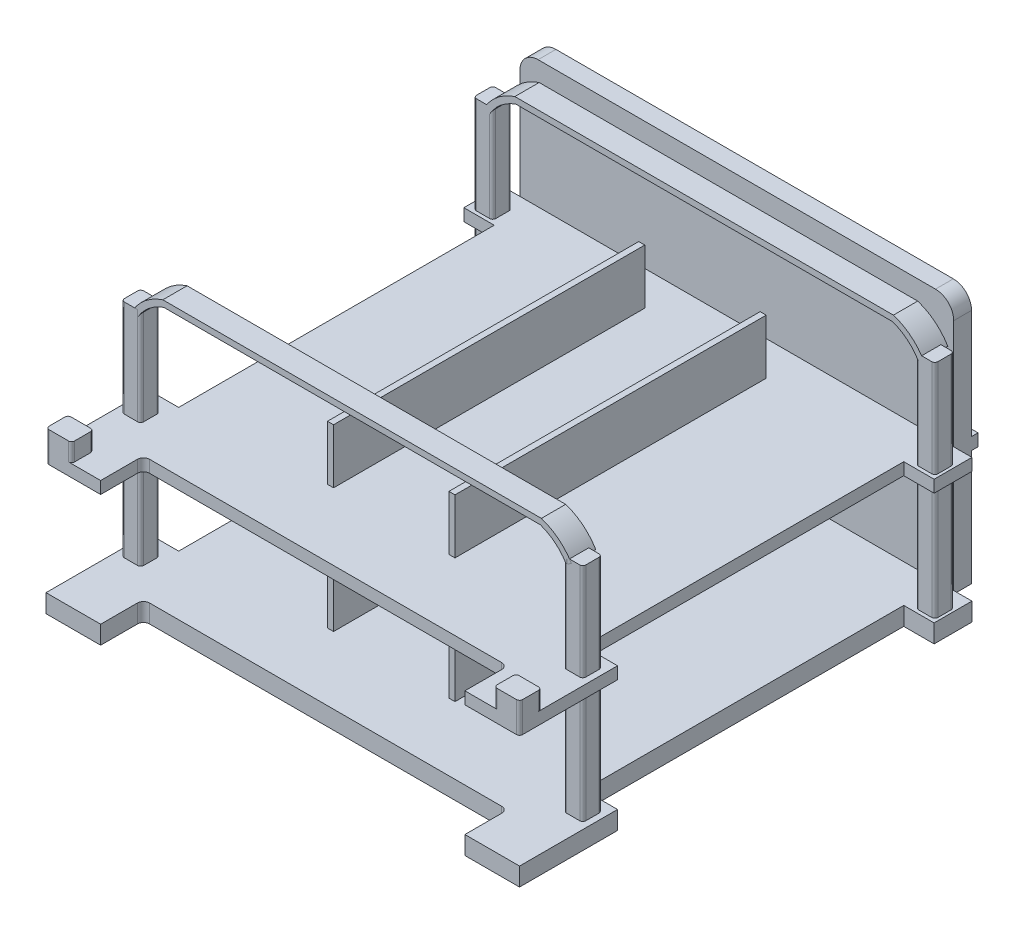
SolidWorks part; units mm, degrees
ref_plane "Front Plane" through (0, 0, 0) normal (0, 0, 1) x (1, 0, 0)
ref_plane "Top Plane" through (0, 0, 0) normal (0, 1, 0) x (1, 0, 0)
ref_plane "Right Plane" through (0, 0, 0) normal (1, 0, 0) x (0, 0, -1)
sketch "Sketch1" plane through (0, 0, 0) normal (0, 1, 0) x (1, 0, 0)
  line L0 (0, 0) -> (9, 0)
  line L1 (9, 0) -> (9, 6.0585)
  line L2 (10, 7.0585) -> (68, 7.0585)
  line L3 (69, 6.0585) -> (69, 0)
  line L4 (69, 0) -> (78, 0)
  line L5 (78, 0) -> (78, 16.147)
  line L6 (78, 16.147) -> (72.4592, 16.147)
  line L7 (72.4592, 16.147) -> (72.4592, 68.829)
  line L8 (72.4592, 68.829) -> (77.4592, 68.829)
  line L9 (77.4592, 68.829) -> (77.4592, 75.0585)
  line L10 (77.4592, 75.0585) -> (0, 75.0585)
  line L11 (0, 75.0585) -> (0, 68.829)
  line L12 (0, 68.829) -> (5, 68.829)
  line L13 (5, 68.829) -> (5, 16.8497)
  line L14 (5, 16.8497) -> (0, 16.8497)
  line L15 (0, 16.8497) -> (0, 0)
  arc A0 (9, 6.0585) -> (10, 7.0585) centre (10, 6.0585) cw
  arc A1 (69, 6.0585) -> (68, 7.0585) centre (68, 6.0585) ccw
  point P19 (9, 7.0585)
  point P22 (69, 7.0585)
  dimension "D7" = 1
  dimension "D8" = 1
  dimension "D1" = 60
  dimension "D2" = 4
  dimension "D3" = 3.4592
  dimension "D4" = 9
  dimension "D5" = 9
  dimension "D6" = 68
extrude "Boss-Extrude1" add sketch "Sketch1" along normal blind 2
sketch "Sketch2" plane through (0, 2, 0) normal (0, 1, 0) x (1, 0, 0)
  line L0 (1, 14.5922) -> (1, 11.4189)
  line L1 (1, 11.4189) -> (4.1733, 11.4189)
  line L2 (4.1733, 11.4189) -> (4.1733, 14.5922)
  line L3 (4.1733, 14.5922) -> (1, 14.5922)
  line L4 (39, 7.0585) -> (39, 14.1654) construction
  line L5 (10, 7.0585) -> (68, 7.0585) construction
  line L6 (73.8267, 11.4189) -> (73.8267, 14.5922)
  line L7 (77, 11.4189) -> (73.8267, 11.4189)
  line L8 (77, 14.5922) -> (77, 11.4189)
  line L9 (73.8267, 14.5922) -> (77, 14.5922)
  line L10 (5, 22.5675) -> (72.4592, 22.5675) construction
  line L11 (5, 68.829) -> (5, 16.8497) construction
  line L12 (72.4592, 16.147) -> (72.4592, 68.829) construction
  line L13 (0, 16.8497) -> (0, 0) construction
  dimension "D1" = 1
extrude "Boss-Extrude2" add sketch "Sketch2" along normal blind 16
sketch "Sketch3" plane through (0, 0, -11.4189) normal (0, 0, 1) x (1, 0, 0)
  line L0 (7.9846, 20.4783) -> (70.0154, 20.4783)
  line L1 (10, 2) -> (68, 2) construction
  line L2 (39, 20.4783) -> (39, -1.4193) construction
  line L3 (1, 18) -> (4.1733, 18) construction
  arc A0 (3.7238, 17) -> (7.9846, 20.4783) centre (10.609, 12.9147) cw
  arc A1 (74.2762, 17) -> (70.0154, 20.4783) centre (67.391, 12.9147) ccw
  point P3 (0, 0)
  point P7 (39, 2)
  point P14 (4.1229, 17)
  point P15 (7.1416, 20.6069)
  point P16 (6.236, 21.0597)
  point P17 (7.9846, 20.4783)
  point P18 (74.2762, 17)
  dimension "D1" = 1
extrude "Extrude-Thin1" add sketch "Sketch3" against normal blind 4 separate body thin thin type one direction wall 1
ref_plane "Plane1" through (0, 0, -42) normal (0, 0, 1) x (1, 0, 0)
mirror "Mirror1" about plane through (0, 0, -42) normal (0, 0, 1) of "Extrude-Thin1", "Boss-Extrude2"
sketch "Sketch4" plane through (0, 0, -69.4078) normal (0, 0, 1) x (1, 0, 0)
  line L0 (7.9846, 20.4783) -> (70.0154, 20.4783) construction
  line L1 (7.9846, 20.4783) -> (70.0154, 20.4783)
  arc A0 (74.2762, 17) -> (70.0154, 20.4783) centre (67.391, 12.9147) ccw construction
  arc A1 (7.9846, 20.4783) -> (3.7238, 17) centre (10.609, 12.9147) ccw construction
  arc A2 (74.2762, 17) -> (70.0154, 20.4783) centre (67.391, 12.9147) ccw
  arc A3 (7.9846, 20.4783) -> (3.7238, 17) centre (10.609, 12.9147) ccw
extrude "Extrude-Thin2" add sketch "Sketch4" against normal blind 4 thin thin type one direction wall 1
ref_plane "Plane2" through (0, -20, 0) normal (0, -1, 0) x (-1, 0, 0)
sketch "Sketch6" plane through (0, -20, 0) normal (0, -1, 0) x (-1, 0, 0)
  line L16 (-9, 6.0585) -> (-9, 0)
  line L17 (-9, 0) -> (0, 0)
  line L18 (0, 0) -> (0, 16.8497)
  line L19 (0, 16.8497) -> (-5, 16.8497)
  line L20 (-5, 16.8497) -> (-5, 68.829)
  line L21 (-5, 68.829) -> (0, 68.829)
  line L22 (0, 68.829) -> (0, 75.0585)
  line L23 (0, 75.0585) -> (-77.4592, 75.0585)
  line L24 (-77.4592, 75.0585) -> (-77.4592, 68.829)
  line L25 (-77.4592, 68.829) -> (-72.4592, 68.829)
  line L26 (-72.4592, 68.829) -> (-72.4592, 16.147)
  line L27 (-72.4592, 16.147) -> (-78, 16.147)
  line L28 (-78, 16.147) -> (-78, 0)
  line L29 (-78, 0) -> (-69, 0)
  line L30 (-69, 0) -> (-69, 6.0585)
  line L31 (-68, 7.0585) -> (-10, 7.0585)
  line L32 (-9, 6.0585) -> (-9, 0)
  line L33 (-9, 0) -> (0, 0)
  line L34 (0, 0) -> (0, 16.8497)
  line L35 (0, 16.8497) -> (-5, 16.8497)
  line L36 (-5, 16.8497) -> (-5, 68.829)
  line L37 (-5, 68.829) -> (0, 68.829)
  line L38 (0, 68.829) -> (0, 75.0585)
  line L39 (0, 75.0585) -> (-77.4592, 75.0585)
  line L40 (-77.4592, 75.0585) -> (-77.4592, 68.829)
  line L41 (-77.4592, 68.829) -> (-72.4592, 68.829)
  line L42 (-72.4592, 68.829) -> (-72.4592, 16.147)
  line L43 (-72.4592, 16.147) -> (-78, 16.147)
  line L44 (-78, 16.147) -> (-78, 0)
  line L45 (-78, 0) -> (-69, 0)
  line L46 (-69, 0) -> (-69, 6.0585)
  line L47 (-68, 7.0585) -> (-10, 7.0585)
  arc A2 (-68, 7.0585) -> (-69, 6.0585) centre (-68, 6.0585) ccw
  arc A3 (-9, 6.0585) -> (-10, 7.0585) centre (-10, 6.0585) ccw
  arc A4 (-68, 7.0585) -> (-69, 6.0585) centre (-68, 6.0585) ccw
  arc A5 (-9, 6.0585) -> (-10, 7.0585) centre (-10, 6.0585) ccw
  dimension "D1" = 0
extrude "Boss-Extrude3" add sketch "Sketch6" against normal mid plane 3 separate body
sketch "Sketch7" plane through (0, -18.5, 0) normal (0, 1, 0) x (1, 0, 0)
  line L0 (73.8267, 69.4078) -> (73.8267, 72.5811) construction
  line L1 (77, 69.4078) -> (73.8267, 69.4078) construction
  line L2 (73.8267, 72.5811) -> (77, 72.5811) construction
  line L3 (77, 72.5811) -> (77, 69.4078) construction
  line L4 (73.8267, 14.5922) -> (73.8267, 11.4189)
  line L5 (77, 14.5922) -> (73.8267, 14.5922)
  line L6 (77, 11.4189) -> (77, 14.5922)
  line L7 (73.8267, 11.4189) -> (77, 11.4189)
  line L8 (73.8267, 14.5922) -> (73.8267, 11.4189)
  line L9 (77, 14.5922) -> (73.8267, 14.5922)
  line L10 (77, 11.4189) -> (77, 14.5922)
  line L11 (73.8267, 11.4189) -> (77, 11.4189)
  line L12 (1, 14.5922) -> (1, 11.4189)
  line L13 (1, 11.4189) -> (4.1733, 11.4189)
  line L14 (4.1733, 11.4189) -> (4.1733, 14.5922)
  line L15 (4.1733, 14.5922) -> (1, 14.5922)
  line L16 (1, 14.5922) -> (1, 11.4189)
  line L17 (1, 11.4189) -> (4.1733, 11.4189)
  line L18 (4.1733, 11.4189) -> (4.1733, 14.5922)
  line L19 (4.1733, 14.5922) -> (1, 14.5922)
  line L24 (73.8267, 69.4078) -> (73.8267, 72.5811)
  line L25 (77, 69.4078) -> (73.8267, 69.4078)
  line L26 (73.8267, 72.5811) -> (77, 72.5811)
  line L27 (77, 72.5811) -> (77, 69.4078)
  line L33 (4.1733, 69.4078) -> (1, 69.4078) construction
  line L34 (4.1733, 72.5811) -> (4.1733, 69.4078) construction
  line L35 (1, 72.5811) -> (4.1733, 72.5811) construction
  line L36 (1, 69.4078) -> (1, 72.5811) construction
  line L37 (4.1733, 69.4078) -> (1, 69.4078)
  line L38 (4.1733, 72.5811) -> (4.1733, 69.4078)
  line L39 (1, 72.5811) -> (4.1733, 72.5811)
  line L40 (1, 69.4078) -> (1, 72.5811)
  dimension "D1" = 0
  dimension "D2" = 0
extrude "Boss-Extrude4" add sketch "Sketch7" along normal up to surface (18.5 mm away) up to face at (38.8798, 0, -28.7819)
sketch "Sketch8" plane through (0, 2, 0) normal (0, 1, 0) x (1, 0, 0)
  line L0 (39, 7.0585) -> (39, 14.1654) construction
  line L1 (0, 0) -> (4.2068, 0)
  line L2 (0, 0) -> (0, 3.6268)
  line L3 (0, 3.6268) -> (4.2068, 3.6268)
  line L4 (4.2068, 0) -> (4.2068, 3.6268)
  line L5 (39, 7.0585) -> (39, 14.1654) construction
  line L6 (78, 3.6268) -> (73.7932, 3.6268)
  line L7 (73.7932, 0) -> (73.7932, 3.6268)
  line L8 (78, 0) -> (73.7932, 0)
  line L9 (78, 0) -> (78, 3.6268)
extrude "Boss-Extrude5" add sketch "Sketch8" along normal blind 3
fillet "Fillet2" radius 0.5 40 edges at (77, -9.25, -11.4189) (1, -9.25, -14.5922) (1, -9.25, -11.4189) (4.1733, -9.25, -11.4189) (73.8267, -9.25, -11.4189) (73.8267, -9.25, -14.5922) (4.1733, -9.25, -14.5922) (77, -9.25, -14.5922) (77, -9.25, -69.4078) (73.8267, -9.25, -69.4078) (73.8267, -9.25, -72.5811) (77, -9.25, -72.5811) (78, 2.5, 0) (73.7932, 3.5, 0) (78, 3.5, -3.6268) (73.7932, 3.5, -3.6268) (73.8267, 10, -11.4189) (73.8267, 10, -14.5922) (77, 10, -14.5922) (77, 10, -11.4189) (73.8267, 9.8384, -72.5811) (73.8267, 9.8384, -69.4078) (77, 10, -72.5811) (77, 10, -69.4078) (4.1733, 9.8384, -72.5811) (4.1733, 9.8384, -69.4078) (1, 10, -72.5811) (1, 10, -69.4078) (4.1733, 10, -14.5922) (4.1733, 10, -11.4189) (1, 10, -14.5922) (1, 10, -11.4189) (0, 3.5, -3.6268) (4.2068, 3.5, -3.6268) (4.2068, 3.5, 0) (0, 2.5, 0) (1, -9.25, -72.5811) (4.1733, -9.25, -72.5811) (4.1733, -9.25, -69.4078) (1, -9.25, -69.4078)
sketch "Sketch9" plane through (0, 0, -75.0585) normal (0, 0, -1) x (-1, 0, 0)
  line L0 (-74.4592, 2) -> (-74.4592, 0)
  line L1 (-77.4592, 2) -> (0, 2) construction
  line L2 (-77.4592, 0) -> (0, 0) construction
  line L3 (-74.4592, 0) -> (-3, 0)
  line L4 (-3, 0) -> (-3, 2)
  line L5 (-3, 2) -> (-74.4592, 2)
  line L6 (-77.4592, 2) -> (-77.4592, 0) construction
  line L7 (0, 2) -> (0, 0) construction
  dimension "D1" = 3
  dimension "D2" = 3
extrude "Boss-Extrude6" add sketch "Sketch9" along normal blind 4
sketch "Sketch10" plane through (0, 2, 0) normal (0, 1, 0) x (1, 0, 0)
  line L0 (3, 75.0585) -> (74.4592, 75.0585)
  line L1 (74.4592, 79.0585) -> (74.4592, 75.0585) construction
  line L2 (3, 79.0585) -> (3, 75.0585) construction
  line L4 (74.4592, 77.9939) -> (74.4592, 75.0585)
  line L5 (3, 77.9939) -> (3, 75.0585)
  line L7 (3, 77.9939) -> (74.4592, 77.9939)
extrude "Boss-Extrude7" add sketch "Sketch10" along normal mid plane 42
fillet "Fillet3" radius 3 2 edges at (74.4592, 23, -76.5262) (3, 23, -76.5262)
sketch "Sketch11" plane through (0, 2, 0) normal (0, 1, 0) x (1, 0, 0)
  line L0 (28.7296, 69.4078) -> (28.7296, 18.1349)
  line L1 (70.1789, 69.4078) -> (7.8211, 69.4078) construction
  line L2 (48.7296, 69.4078) -> (48.7296, 18.1349)
  line L3 (28.7296, 43.7714) -> (5, 43.7714) construction
  line L4 (5, 68.829) -> (5, 16.8497) construction
  line L5 (48.7296, 43.7714) -> (72.4592, 43.7714) construction
  line L6 (72.4592, 16.147) -> (72.4592, 68.829) construction
  dimension "D1" = 20
extrude "Extrude-Thin3" add sketch "Sketch11" along normal blind 9 thin thin type mid plane wall 1
pattern_linear "LPattern1" count 2 spacing 21 along (0, -1, 0) of "Extrude-Thin3"
